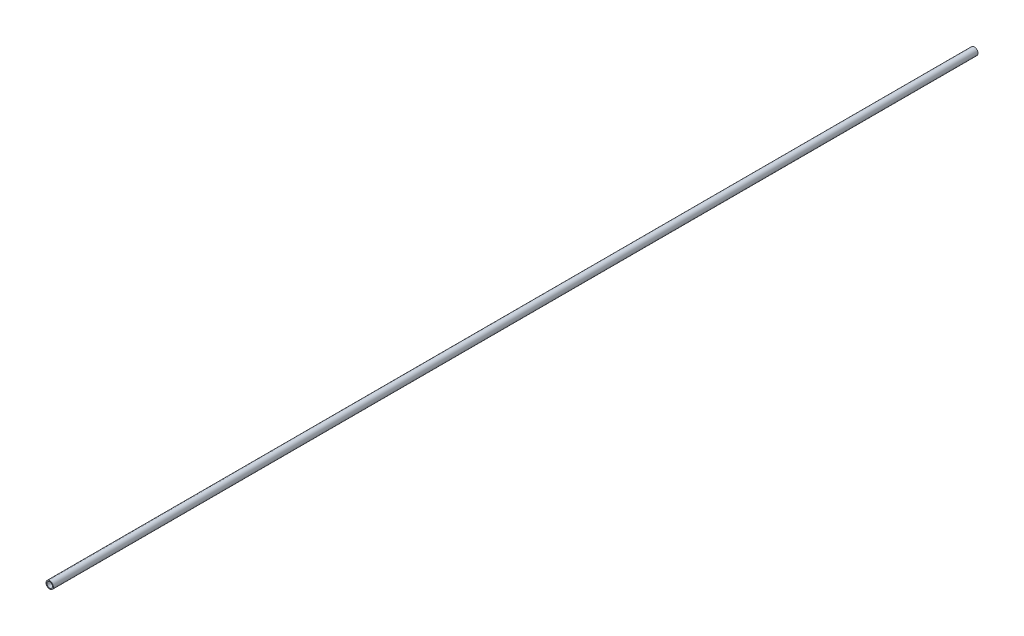
SolidWorks part; units mm, degrees
material "Плетеная трубка"
ref_plane "Front Plane" through (0, 0, 0) normal (0, 0, 1) x (1, 0, 0)
ref_plane "Top Plane" through (0, 0, 0) normal (0, 1, 0) x (1, 0, 0)
ref_plane "Right Plane" through (0, 0, 0) normal (1, 0, 0) x (0, 0, -1)
sketch "Sketch1" plane through (0, 0, 0) normal (0, 0, 1) x (1, 0, 0)
  circle A0 centre (0, 0) radius 4
  dimension "D1" = 8
extrude "Boss-Extrude1" add sketch "Sketch1" along normal mid plane 1000
shell "Shell1" thickness 1
